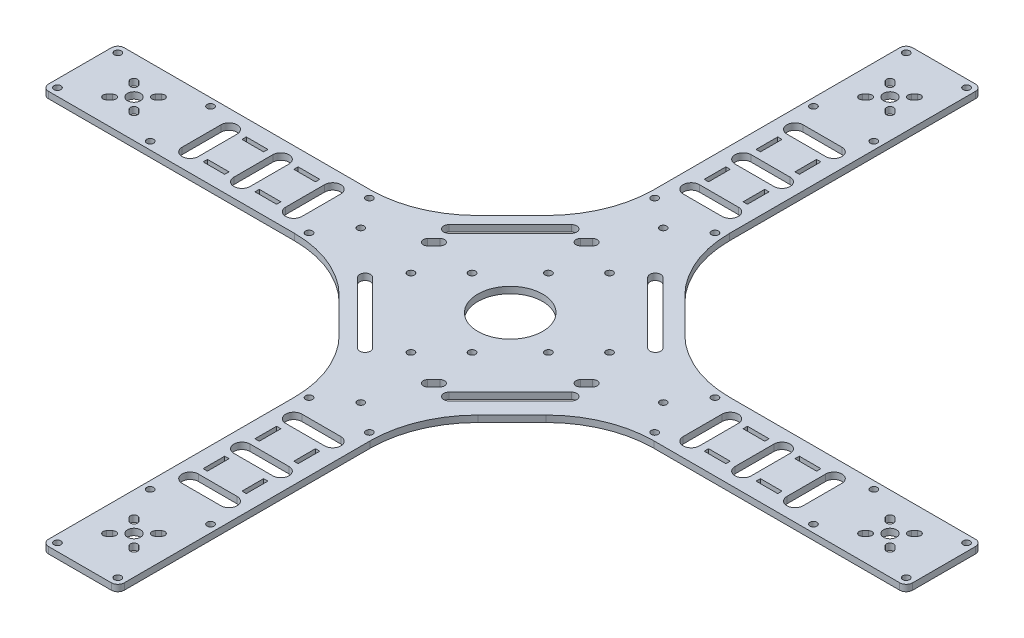
SolidWorks part; units mm, degrees
ref_plane "前视基准面" through (0, 0, 0) normal (0, 0, 1) x (1, 0, 0)
ref_plane "上视基准面" through (0, 0, 0) normal (0, 1, 0) x (1, 0, 0)
ref_plane "右视基准面" through (0, 0, 0) normal (1, 0, 0) x (0, 0, -1)
other "Configuration Table"
sketch "基本底盘" plane through (0, 0, 0) normal (0, 1, 0) x (1, 0, 0)
  line L0 (0, 0) -> (0, -350) construction
  line L1 (4.9497, -4.9497) -> (6.364, -6.364) construction
  line L4 (6.0811, -3.8184) -> (7.4953, -5.2326)
  line L5 (3.8184, -6.0811) -> (5.2326, -7.4953)
  line L6 (-17.5, 25) -> (17.5, 25)
  line L9 (-4.9497, -4.9497) -> (-6.364, -6.364) construction
  line L10 (-3.8184, -6.0811) -> (-5.2326, -7.4953)
  line L11 (-6.0811, -3.8184) -> (-7.4953, -5.2326)
  line L12 (-17.5, 25) -> (-17.5, -25)
  line L15 (-4.9497, 4.9497) -> (-6.364, 6.364) construction
  line L16 (-6.0811, 3.8184) -> (-7.4953, 5.2326)
  line L17 (-3.8184, 6.0811) -> (-5.2326, 7.4953)
  line L18 (17.5, 25) -> (17.5, -25)
  line L21 (4.9497, 4.9497) -> (6.364, 6.364) construction
  line L22 (3.8184, 6.0811) -> (5.2326, 7.4953)
  line L23 (6.0811, 3.8184) -> (7.4953, 5.2326)
  line L24 (0, -25) -> (0, -35)
  line L25 (-9, -35) -> (9, -35) construction
  line L26 (-9, -59) -> (9, -59) construction
  line L27 (-17.5, -25) -> (17.5, -25) construction
  line L28 (-17.5, 25) -> (17.5, -25) construction
  line L29 (17.5, 25) -> (-17.5, -25) construction
  line L30 (-17.5, 25) -> (-13.9645, 21.4645)
  line L31 (-17.5, 0) -> (17.5, 0) construction
  line L32 (-80, -175) -> (80, -175)
  line L33 (0, -95) -> (0, -255)
  line L34 (-32.1447, -127.1447) -> (-47.8553, -142.8553)
  line L35 (32.1447, -222.8553) -> (47.8553, -207.1447)
  line L36 (47.8553, -142.8553) -> (32.1447, -127.1447)
  line L37 (-47.8553, -207.1447) -> (-32.1447, -222.8553)
  line L38 (-13.9645, -21.4645) -> (-13.9645, -95) construction
  line L39 (-17.5, -25) -> (-17.5, -91.7893)
  line L40 (17.5, -25) -> (17.5, -91.7893)
  line L41 (0, -95) -> (0, -105)
  line L42 (-9, -31.25) -> (9, -31.25)
  line L43 (-9, -38.75) -> (9, -38.75)
  line L44 (-9, -55.25) -> (9, -55.25)
  line L45 (-9, -62.75) -> (9, -62.75)
  line L46 (-9, -83) -> (9, -83) construction
  line L47 (-9, -79.25) -> (9, -79.25)
  line L48 (-9, -86.75) -> (9, -86.75)
  line L49 (9, -38.75) -> (9, -55.25)
  line L50 (8, -42) -> (10, -42)
  line L51 (8, -42) -> (8, -52)
  line L52 (10, -42) -> (10, -52)
  line L53 (8, -52) -> (10, -52)
  line L54 (8, -42) -> (10, -52) construction
  line L55 (10, -42) -> (8, -52) construction
  line L56 (8, -66) -> (10, -76) construction
  line L57 (10, -66) -> (8, -76) construction
  line L58 (8, -66) -> (10, -66)
  line L59 (8, -66) -> (8, -76)
  line L60 (8, -76) -> (10, -76)
  line L61 (10, -66) -> (10, -76)
  line L62 (-8, -66) -> (-8, -76)
  line L63 (-8, -76) -> (-10, -76)
  line L64 (-10, -66) -> (-10, -76)
  line L65 (-8, -66) -> (-10, -66)
  line L66 (-8, -52) -> (-10, -52)
  line L67 (-8, -42) -> (-8, -52)
  line L68 (-8, -42) -> (-10, -42)
  line L69 (-10, -42) -> (-10, -52)
  line L70 (200, -157.5) -> (200, -192.5)
  line L71 (200, -157.5) -> (150, -157.5)
  line L72 (200, -192.5) -> (150, -192.5)
  line L73 (150, -175) -> (140, -175)
  line L74 (200, -157.5) -> (196.4645, -161.0355)
  line L75 (136.25, -184) -> (119.75, -184)
  line L76 (133, -183) -> (133, -185)
  line L77 (133, -183) -> (123, -183)
  line L78 (133, -185) -> (123, -185)
  line L79 (123, -183) -> (123, -185)
  line L80 (109, -183) -> (109, -185)
  line L81 (109, -183) -> (99, -183)
  line L82 (99, -183) -> (99, -185)
  line L83 (109, -185) -> (99, -185)
  line L84 (109, -167) -> (99, -167)
  line L85 (99, -167) -> (99, -165)
  line L86 (109, -165) -> (99, -165)
  line L87 (109, -167) -> (109, -165)
  line L88 (123, -167) -> (123, -165)
  line L89 (133, -167) -> (123, -167)
  line L90 (133, -167) -> (133, -165)
  line L91 (133, -165) -> (123, -165)
  line L92 (150, -157.5) -> (150, -192.5) construction
  line L93 (200, -157.5) -> (150, -192.5) construction
  line L94 (200, -192.5) -> (150, -157.5) construction
  line L95 (175, -157.5) -> (175, -192.5) construction
  line L96 (153.5355, -161.0355) -> (80, -161.0355) construction
  line L97 (133, -183) -> (123, -185) construction
  line L98 (133, -185) -> (123, -183) construction
  line L99 (109, -183) -> (99, -185) construction
  line L100 (109, -185) -> (99, -183) construction
  line L101 (150, -157.5) -> (83.2107, -157.5)
  line L102 (150, -192.5) -> (83.2107, -192.5)
  line L103 (170.0503, -179.9497) -> (168.636, -181.364) construction
  line L104 (171.1816, -181.0811) -> (169.7674, -182.4953)
  line L105 (168.9189, -178.8184) -> (167.5047, -180.2326)
  line L106 (170.0503, -170.0503) -> (168.636, -168.636) construction
  line L107 (168.9189, -171.1816) -> (167.5047, -169.7674)
  line L108 (171.1816, -168.9189) -> (169.7674, -167.5047)
  line L109 (179.9497, -170.0503) -> (181.364, -168.636) construction
  line L110 (178.8184, -168.9189) -> (180.2326, -167.5047)
  line L111 (181.0811, -171.1816) -> (182.4953, -169.7674)
  line L112 (179.9497, -179.9497) -> (181.364, -181.364) construction
  line L113 (181.0811, -178.8184) -> (182.4953, -180.2326)
  line L114 (178.8184, -181.0811) -> (180.2326, -182.4953)
  line L115 (140, -166) -> (140, -184) construction
  line L116 (143.75, -166) -> (143.75, -184)
  line L117 (136.25, -166) -> (136.25, -184)
  line L118 (116, -166) -> (116, -184) construction
  line L119 (119.75, -166) -> (119.75, -184)
  line L120 (112.25, -166) -> (112.25, -184)
  line L121 (92, -166) -> (92, -184) construction
  line L122 (95.75, -166) -> (95.75, -184)
  line L123 (88.25, -166) -> (88.25, -184)
  line L124 (17.5, -375) -> (-17.5, -375)
  line L125 (17.5, -375) -> (17.5, -325)
  line L126 (-17.5, -375) -> (-17.5, -325)
  line L127 (0, -325) -> (0, -315)
  line L128 (17.5, -375) -> (13.9645, -371.4645)
  line L129 (-9, -311.25) -> (-9, -294.75)
  line L130 (-8, -308) -> (-10, -308)
  line L131 (-8, -308) -> (-8, -298)
  line L132 (-10, -308) -> (-10, -298)
  line L133 (-8, -298) -> (-10, -298)
  line L134 (-8, -284) -> (-10, -284)
  line L135 (-8, -284) -> (-8, -274)
  line L136 (-8, -274) -> (-10, -274)
  line L137 (-10, -284) -> (-10, -274)
  line L138 (8, -284) -> (8, -274)
  line L139 (8, -274) -> (10, -274)
  line L140 (10, -284) -> (10, -274)
  line L141 (8, -284) -> (10, -284)
  line L142 (8, -298) -> (10, -298)
  line L143 (8, -308) -> (8, -298)
  line L144 (8, -308) -> (10, -308)
  line L145 (10, -308) -> (10, -298)
  line L146 (17.5, -325) -> (-17.5, -325) construction
  line L147 (17.5, -375) -> (-17.5, -325) construction
  line L148 (-17.5, -375) -> (17.5, -325) construction
  line L149 (17.5, -350) -> (-17.5, -350) construction
  line L150 (13.9645, -328.5355) -> (13.9645, -255) construction
  line L151 (-8, -308) -> (-10, -298) construction
  line L152 (-10, -308) -> (-8, -298) construction
  line L153 (-8, -284) -> (-10, -274) construction
  line L154 (-10, -284) -> (-8, -274) construction
  line L155 (17.5, -325) -> (17.5, -258.2107)
  line L156 (-17.5, -325) -> (-17.5, -258.2107)
  line L157 (-4.9497, -345.0503) -> (-6.364, -343.636) construction
  line L158 (-6.0811, -346.1816) -> (-7.4953, -344.7674)
  line L159 (-3.8184, -343.9189) -> (-5.2326, -342.5047)
  line L160 (4.9497, -345.0503) -> (6.364, -343.636) construction
  line L161 (3.8184, -343.9189) -> (5.2326, -342.5047)
  line L162 (6.0811, -346.1816) -> (7.4953, -344.7674)
  line L163 (4.9497, -354.9497) -> (6.364, -356.364) construction
  line L164 (6.0811, -353.8184) -> (7.4953, -355.2326)
  line L165 (3.8184, -356.0811) -> (5.2326, -357.4953)
  line L166 (-4.9497, -354.9497) -> (-6.364, -356.364) construction
  line L167 (-3.8184, -356.0811) -> (-5.2326, -357.4953)
  line L168 (-6.0811, -353.8184) -> (-7.4953, -355.2326)
  line L169 (9, -315) -> (-9, -315) construction
  line L170 (9, -318.75) -> (-9, -318.75)
  line L171 (9, -311.25) -> (-9, -311.25)
  line L172 (9, -291) -> (-9, -291) construction
  line L173 (9, -294.75) -> (-9, -294.75)
  line L174 (9, -287.25) -> (-9, -287.25)
  line L175 (9, -267) -> (-9, -267) construction
  line L176 (9, -270.75) -> (-9, -270.75)
  line L177 (9, -263.25) -> (-9, -263.25)
  line L178 (-200, -192.5) -> (-200, -157.5)
  line L179 (-200, -192.5) -> (-150, -192.5)
  line L180 (-200, -157.5) -> (-150, -157.5)
  line L181 (-150, -175) -> (-140, -175)
  line L182 (-200, -192.5) -> (-196.4645, -188.9645)
  line L183 (-136.25, -166) -> (-119.75, -166)
  line L184 (-133, -167) -> (-133, -165)
  line L185 (-133, -167) -> (-123, -167)
  line L186 (-133, -165) -> (-123, -165)
  line L187 (-123, -167) -> (-123, -165)
  line L188 (-109, -167) -> (-109, -165)
  line L189 (-109, -167) -> (-99, -167)
  line L190 (-99, -167) -> (-99, -165)
  line L191 (-109, -165) -> (-99, -165)
  line L192 (-109, -183) -> (-99, -183)
  line L193 (-99, -183) -> (-99, -185)
  line L194 (-109, -185) -> (-99, -185)
  line L195 (-109, -183) -> (-109, -185)
  line L196 (-123, -183) -> (-123, -185)
  line L197 (-133, -183) -> (-123, -183)
  line L198 (-133, -183) -> (-133, -185)
  line L199 (-133, -185) -> (-123, -185)
  line L200 (-150, -192.5) -> (-150, -157.5) construction
  line L201 (-200, -192.5) -> (-150, -157.5) construction
  line L202 (-200, -157.5) -> (-150, -192.5) construction
  line L203 (-175, -192.5) -> (-175, -157.5) construction
  line L204 (-153.5355, -188.9645) -> (-80, -188.9645) construction
  line L205 (-133, -167) -> (-123, -165) construction
  line L206 (-133, -165) -> (-123, -167) construction
  line L207 (-109, -167) -> (-99, -165) construction
  line L208 (-109, -165) -> (-99, -167) construction
  line L209 (-150, -192.5) -> (-83.2107, -192.5)
  line L210 (-150, -157.5) -> (-83.2107, -157.5)
  line L211 (-170.0503, -170.0503) -> (-168.636, -168.636) construction
  line L212 (-171.1816, -168.9189) -> (-169.7674, -167.5047)
  line L213 (-168.9189, -171.1816) -> (-167.5047, -169.7674)
  line L214 (-170.0503, -179.9497) -> (-168.636, -181.364) construction
  line L215 (-168.9189, -178.8184) -> (-167.5047, -180.2326)
  line L216 (-171.1816, -181.0811) -> (-169.7674, -182.4953)
  line L217 (-179.9497, -179.9497) -> (-181.364, -181.364) construction
  line L218 (-178.8184, -181.0811) -> (-180.2326, -182.4953)
  line L219 (-181.0811, -178.8184) -> (-182.4953, -180.2326)
  line L220 (-179.9497, -170.0503) -> (-181.364, -168.636) construction
  line L221 (-181.0811, -171.1816) -> (-182.4953, -169.7674)
  line L222 (-178.8184, -168.9189) -> (-180.2326, -167.5047)
  line L223 (-140, -184) -> (-140, -166) construction
  line L224 (-143.75, -184) -> (-143.75, -166)
  line L225 (-136.25, -184) -> (-136.25, -166)
  line L226 (-116, -184) -> (-116, -166) construction
  line L227 (-119.75, -184) -> (-119.75, -166)
  line L228 (-112.25, -184) -> (-112.25, -166)
  line L229 (-92, -184) -> (-92, -166) construction
  line L230 (-95.75, -184) -> (-95.75, -166)
  line L231 (-88.25, -184) -> (-88.25, -166)
  line L232 (0, -95) -> (-32.1447, -127.1447)
  line L233 (0, -95) -> (32.1447, -127.1447)
  line L234 (47.8553, -142.8553) -> (80, -175)
  line L235 (47.8553, -207.1447) -> (80, -175)
  line L236 (-80, -175) -> (-47.8553, -207.1447)
  line L237 (-80, -175) -> (-47.8553, -142.8553)
  line L238 (-32.1447, -222.8553) -> (0, -255)
  line L239 (0, -255) -> (32.1447, -222.8553)
  circle A0 centre (0, 0) radius 8 construction
  arc A3 (6.0811, -3.8184) -> (3.8184, -6.0811) centre (4.9497, -4.9497) ccw
  arc A4 (5.2326, -7.4953) -> (7.4953, -5.2326) centre (6.364, -6.364) ccw
  arc A7 (-3.8184, -6.0811) -> (-6.0811, -3.8184) centre (-4.9497, -4.9497) ccw
  arc A8 (-7.4953, -5.2326) -> (-5.2326, -7.4953) centre (-6.364, -6.364) ccw
  arc A11 (-6.0811, 3.8184) -> (-3.8184, 6.0811) centre (-4.9497, 4.9497) ccw
  arc A12 (-5.2326, 7.4953) -> (-7.4953, 5.2326) centre (-6.364, 6.364) ccw
  arc A15 (3.8184, 6.0811) -> (6.0811, 3.8184) centre (4.9497, 4.9497) ccw
  arc A16 (7.4953, 5.2326) -> (5.2326, 7.4953) centre (6.364, 6.364) ccw
  circle A17 centre (0, 0) radius 14 construction
  arc A18 (-9, -31.25) -> (-9, -38.75) centre (-9, -35) ccw
  arc A19 (9, -38.75) -> (9, -31.25) centre (9, -35) ccw
  circle A20 centre (0, 0) radius 3
  circle A21 centre (0, 0) radius 88.9 construction
  circle A22 centre (0, 0) radius 64.77 construction
  circle A23 centre (-13.9645, 21.4645) radius 1.6
  circle A24 centre (13.9645, 21.4645) radius 1.6
  circle A25 centre (13.9645, -21.4645) radius 1.6
  circle A26 centre (-13.9645, -21.4645) radius 1.6
  circle A27 centre (-13.9645, -95) radius 1.6
  circle A28 centre (13.9645, -95) radius 1.6
  circle A29 centre (0, -105) radius 1.6
  arc A30 (-9, -55.25) -> (-9, -62.75) centre (-9, -59) ccw
  arc A31 (9, -62.75) -> (9, -55.25) centre (9, -59) ccw
  arc A32 (-9, -79.25) -> (-9, -86.75) centre (-9, -83) ccw
  arc A33 (9, -86.75) -> (9, -79.25) centre (9, -83) ccw
  circle A34 centre (175, -175) radius 3
  circle A35 centre (196.4645, -161.0355) radius 1.6
  circle A36 centre (196.4645, -188.9645) radius 1.6
  circle A37 centre (153.5355, -188.9645) radius 1.6
  circle A38 centre (153.5355, -161.0355) radius 1.6
  circle A39 centre (80, -161.0355) radius 1.6
  circle A40 centre (80, -188.9645) radius 1.6
  circle A41 centre (175, -175) radius 8 construction
  circle A42 centre (175, -175) radius 14 construction
  circle A43 centre (175, -175) radius 88.9 construction
  circle A44 centre (175, -175) radius 64.77 construction
  circle A45 centre (70, -175) radius 1.6
  arc A46 (171.1816, -181.0811) -> (168.9189, -178.8184) centre (170.0503, -179.9497) ccw
  arc A47 (167.5047, -180.2326) -> (169.7674, -182.4953) centre (168.636, -181.364) ccw
  arc A48 (168.9189, -171.1816) -> (171.1816, -168.9189) centre (170.0503, -170.0503) ccw
  arc A49 (169.7674, -167.5047) -> (167.5047, -169.7674) centre (168.636, -168.636) ccw
  arc A50 (178.8184, -168.9189) -> (181.0811, -171.1816) centre (179.9497, -170.0503) ccw
  arc A51 (182.4953, -169.7674) -> (180.2326, -167.5047) centre (181.364, -168.636) ccw
  arc A52 (181.0811, -178.8184) -> (178.8184, -181.0811) centre (179.9497, -179.9497) ccw
  arc A53 (180.2326, -182.4953) -> (182.4953, -180.2326) centre (181.364, -181.364) ccw
  arc A54 (143.75, -166) -> (136.25, -166) centre (140, -166) ccw
  arc A55 (136.25, -184) -> (143.75, -184) centre (140, -184) ccw
  arc A56 (119.75, -166) -> (112.25, -166) centre (116, -166) ccw
  arc A57 (112.25, -184) -> (119.75, -184) centre (116, -184) ccw
  arc A58 (95.75, -166) -> (88.25, -166) centre (92, -166) ccw
  arc A59 (88.25, -184) -> (95.75, -184) centre (92, -184) ccw
  circle A60 centre (0, -350) radius 3
  circle A61 centre (13.9645, -371.4645) radius 1.6
  circle A62 centre (-13.9645, -371.4645) radius 1.6
  circle A63 centre (-13.9645, -328.5355) radius 1.6
  circle A64 centre (13.9645, -328.5355) radius 1.6
  circle A65 centre (13.9645, -255) radius 1.6
  circle A66 centre (-13.9645, -255) radius 1.6
  circle A67 centre (0, -350) radius 8 construction
  circle A68 centre (0, -350) radius 14 construction
  circle A69 centre (0, -350) radius 88.9 construction
  circle A70 centre (0, -350) radius 64.77 construction
  circle A71 centre (0, -245) radius 1.6
  arc A72 (-6.0811, -346.1816) -> (-3.8184, -343.9189) centre (-4.9497, -345.0503) ccw
  arc A73 (-5.2326, -342.5047) -> (-7.4953, -344.7674) centre (-6.364, -343.636) ccw
  arc A74 (3.8184, -343.9189) -> (6.0811, -346.1816) centre (4.9497, -345.0503) ccw
  arc A75 (7.4953, -344.7674) -> (5.2326, -342.5047) centre (6.364, -343.636) ccw
  arc A76 (6.0811, -353.8184) -> (3.8184, -356.0811) centre (4.9497, -354.9497) ccw
  arc A77 (5.2326, -357.4953) -> (7.4953, -355.2326) centre (6.364, -356.364) ccw
  arc A78 (-3.8184, -356.0811) -> (-6.0811, -353.8184) centre (-4.9497, -354.9497) ccw
  arc A79 (-7.4953, -355.2326) -> (-5.2326, -357.4953) centre (-6.364, -356.364) ccw
  arc A80 (9, -318.75) -> (9, -311.25) centre (9, -315) ccw
  arc A81 (-9, -311.25) -> (-9, -318.75) centre (-9, -315) ccw
  arc A82 (9, -294.75) -> (9, -287.25) centre (9, -291) ccw
  arc A83 (-9, -287.25) -> (-9, -294.75) centre (-9, -291) ccw
  arc A84 (9, -270.75) -> (9, -263.25) centre (9, -267) ccw
  arc A85 (-9, -263.25) -> (-9, -270.75) centre (-9, -267) ccw
  circle A86 centre (-175, -175) radius 3
  circle A87 centre (-196.4645, -188.9645) radius 1.6
  circle A88 centre (-196.4645, -161.0355) radius 1.6
  circle A89 centre (-153.5355, -161.0355) radius 1.6
  circle A90 centre (-153.5355, -188.9645) radius 1.6
  circle A91 centre (-80, -188.9645) radius 1.6
  circle A92 centre (-80, -161.0355) radius 1.6
  circle A93 centre (-175, -175) radius 8 construction
  circle A94 centre (-175, -175) radius 14 construction
  circle A95 centre (-175, -175) radius 88.9 construction
  circle A96 centre (-175, -175) radius 64.77 construction
  circle A97 centre (-70, -175) radius 1.6
  arc A98 (-171.1816, -168.9189) -> (-168.9189, -171.1816) centre (-170.0503, -170.0503) ccw
  arc A99 (-167.5047, -169.7674) -> (-169.7674, -167.5047) centre (-168.636, -168.636) ccw
  arc A100 (-168.9189, -178.8184) -> (-171.1816, -181.0811) centre (-170.0503, -179.9497) ccw
  arc A101 (-169.7674, -182.4953) -> (-167.5047, -180.2326) centre (-168.636, -181.364) ccw
  arc A102 (-178.8184, -181.0811) -> (-181.0811, -178.8184) centre (-179.9497, -179.9497) ccw
  arc A103 (-182.4953, -180.2326) -> (-180.2326, -182.4953) centre (-181.364, -181.364) ccw
  arc A104 (-181.0811, -171.1816) -> (-178.8184, -168.9189) centre (-179.9497, -170.0503) ccw
  arc A105 (-180.2326, -167.5047) -> (-182.4953, -169.7674) centre (-181.364, -168.636) ccw
  arc A106 (-143.75, -184) -> (-136.25, -184) centre (-140, -184) ccw
  arc A107 (-136.25, -166) -> (-143.75, -166) centre (-140, -166) ccw
  arc A108 (-119.75, -184) -> (-112.25, -184) centre (-116, -184) ccw
  arc A109 (-112.25, -166) -> (-119.75, -166) centre (-116, -166) ccw
  arc A110 (-95.75, -184) -> (-88.25, -184) centre (-92, -184) ccw
  arc A111 (-88.25, -166) -> (-95.75, -166) centre (-92, -166) ccw
  arc A112 (17.5, -258.2107) -> (32.1447, -222.8553) centre (67.5, -258.2107) cw
  arc A113 (-17.5, -258.2107) -> (-32.1447, -222.8553) centre (-67.5, -258.2107) ccw
  arc A114 (47.8553, -142.8553) -> (83.2107, -157.5) centre (83.2107, -107.5) ccw
  arc A115 (83.2107, -192.5) -> (47.8553, -207.1447) centre (83.2107, -242.5) ccw
  arc A116 (-47.8553, -207.1447) -> (-83.2107, -192.5) centre (-83.2107, -242.5) ccw
  arc A117 (-47.8553, -142.8553) -> (-83.2107, -157.5) centre (-83.2107, -107.5) cw
  arc A118 (32.1447, -127.1447) -> (17.5, -91.7893) centre (67.5, -91.7893) cw
  arc A119 (-32.1447, -127.1447) -> (-17.5, -91.7893) centre (-67.5, -91.7893) ccw
  point P14 (5.6569, -5.6569)
  point P28 (-5.6569, -5.6569)
  point P34 (0, 0)
  point P42 (-5.6569, 5.6569)
  point P48 (0, -175)
  point P53 (0, -175)
  point P56 (5.6569, 5.6569)
  point P61 (0, 0)
  point P63 (0, 8)
  point P73 (0, -35)
  point P80 (0, -59)
  point P87 (0, -83)
  point P93 (9, -47)
  point P95 (9, -71)
  point P125 (169.3431, -180.6569)
  point P139 (169.3431, -169.3431)
  point P145 (175, -175)
  point P152 (180.6569, -169.3431)
  point P161 (180.6569, -180.6569)
  point P166 (175, -175)
  point P177 (140, -175)
  point P184 (116, -175)
  point P191 (92, -175)
  point P197 (128, -184)
  point P199 (104, -184)
  point P226 (-5.6569, -344.3431)
  point P240 (5.6569, -344.3431)
  point P246 (0, -350)
  point P253 (5.6569, -355.6569)
  point P262 (-5.6569, -355.6569)
  point P267 (0, -350)
  point P278 (0, -315)
  point P285 (0, -291)
  point P292 (0, -267)
  point P298 (-9, -303)
  point P300 (-9, -279)
  point P327 (-169.3431, -169.3431)
  point P341 (-169.3431, -180.6569)
  point P347 (-175, -175)
  point P354 (-180.6569, -180.6569)
  point P363 (-180.6569, -169.3431)
  point P368 (-175, -175)
  point P379 (-140, -175)
  point P386 (-116, -175)
  point P393 (-92, -175)
  point P399 (-128, -166)
  point P401 (-104, -166)
  point P416 (0, -175)
  dimension "D1" = 16
  dimension "D3" = 28
  dimension "D2" = 6
  dimension "D4" = 350
  dimension "D5" = 129.54
  dimension "D9" = 3.2
  dimension "D11" = 3.2
  dimension "D12" = 10
  dimension "D13" = 3.2
  dimension "D14" = 10
  dimension "D15" = 3
  dimension "D20" = 50
  dimension "D6" = 35
  dimension "D7" = 50
  dimension "D8" = 5
  dimension "D10" = 2
  dimension "D16" = 2
  dimension "D17" = 10
  dimension "D18" = 2
  dimension "D19" = 4
extrude "凸台-拉伸1" add sketch "基本底盘" along normal blind 3
fillet "圆角3" radius 3 8 edges at (200, 1.5, 157.5) (200, 1.5, 192.5) (17.5, 1.5, 375) (-17.5, 1.5, 375) (-200, 1.5, 192.5) (-200, 1.5, 157.5) (-17.5, 1.5, -25) (17.5, 1.5, -25)
sketch "草图1" plane through (0, 3, 0) normal (0, 1, 0) x (1, 0, 0)
  line L0 (-43.8547, -181.4697) -> (5.6428, -131.9722) construction
  line L1 (-43.8547, -181.4697) -> (-8.4994, -216.825) construction
  line L2 (5.6428, -131.9722) -> (40.9981, -167.3275) construction
  line L3 (-8.4994, -216.825) -> (40.9981, -167.3275) construction
  line L4 (-43.8547, -181.4697) -> (40.9981, -167.3275) construction
  line L5 (5.6428, -131.9722) -> (-8.4994, -216.825) construction
  line L6 (-43.8547, -181.4697) -> (-39.3043, -186.0201)
  line L9 (-42.0869, -183.2374) -> (-10.2671, -215.0572)
  line L10 (-42.0869, -183.2374) -> (-40.3192, -181.4697)
  line L11 (-26.177, -199.1473) -> (-1.4283, -174.3986) construction
  line L12 (-40.3192, -181.4697) -> (-8.4994, -149.6499) construction
  line L13 (-1.4283, -174.3986) -> (16.2494, -192.0763) construction
  line L14 (16.2494, -192.0763) -> (37.4626, -213.2895)
  line L15 (9.1783, -220.3605) -> (44.5336, -185.0052)
  line L16 (45.9478, -183.591) -> (43.1194, -186.4194) construction
  line L17 (-48.8045, -165.2062) -> (-45.976, -162.3778) construction
  line L18 (47.4328, -185.0759) -> (44.6043, -187.9043)
  line L19 (44.4629, -182.1061) -> (41.6345, -184.9345)
  line L20 (7.7641, -221.7748) -> (10.5925, -218.9463) construction
  line L21 (6.2792, -220.2898) -> (9.1076, -217.4614)
  line L22 (9.249, -223.2597) -> (12.0774, -220.4313)
  line L23 (-47.3195, -166.6911) -> (-44.4911, -163.8627)
  line L24 (-50.2894, -163.7213) -> (-47.461, -160.8929)
  line L25 (-10.6207, -127.0225) -> (-13.4491, -129.8509) construction
  line L26 (-12.1056, -125.5375) -> (-14.934, -128.366)
  line L27 (-9.1358, -128.5074) -> (-11.9642, -131.3358)
  line L28 (-26.177, -199.1473) -> (-35.0159, -207.9862)
  line L29 (-49.158, -193.844) -> (-20.8737, -222.1283) construction
  line L31 (-47.3902, -192.0763) -> (-19.106, -220.3605)
  line L32 (-50.9258, -195.6118) -> (-22.6415, -223.8961)
  line L34 (-20.8737, -126.6689) -> (-49.158, -154.9532) construction
  line L37 (-19.106, -128.4367) -> (-47.3902, -156.7209)
  line L40 (-22.6415, -124.9011) -> (-50.9258, -153.1854)
  line L41 (46.3014, -154.9532) -> (18.0171, -126.6689) construction
  line L42 (44.5336, -156.7209) -> (16.2494, -128.4367)
  line L43 (48.0692, -153.1854) -> (19.7849, -124.9011)
  line L44 (18.0171, -222.1283) -> (46.3014, -193.844) construction
  line L45 (16.2494, -220.3605) -> (44.5336, -192.0763)
  line L46 (19.7849, -223.8961) -> (48.0692, -195.6118)
  circle A1 centre (-40.3192, -181.4697) radius 1.6
  circle A2 centre (-8.4994, -213.2895) radius 1.6
  circle A3 centre (-8.4994, -149.6499) radius 1.6
  circle A4 centre (23.3204, -181.4697) radius 1.6
  circle A5 centre (37.4626, -167.3275) radius 1.6
  circle A6 centre (5.6428, -135.5077) radius 1.6
  circle A7 centre (-26.177, -167.3275) radius 1.6
  circle A8 centre (5.6428, -199.1473) radius 1.6
  arc A9 (47.4328, -185.0759) -> (44.4629, -182.1061) centre (45.9478, -183.591) ccw
  arc A10 (41.6345, -184.9345) -> (44.6043, -187.9043) centre (43.1194, -186.4194) ccw
  arc A11 (6.2792, -220.2898) -> (9.249, -223.2597) centre (7.7641, -221.7748) ccw
  arc A12 (12.0774, -220.4313) -> (9.1076, -217.4614) centre (10.5925, -218.9463) ccw
  arc A13 (-47.3195, -166.6911) -> (-50.2894, -163.7213) centre (-48.8045, -165.2062) cw
  arc A14 (-47.461, -160.8929) -> (-44.4911, -163.8627) centre (-45.976, -162.3778) cw
  arc A15 (-12.1056, -125.5375) -> (-9.1358, -128.5074) centre (-10.6207, -127.0225) cw
  arc A16 (-11.9642, -131.3358) -> (-14.934, -128.366) centre (-13.4491, -129.8509) cw
  circle A17 centre (-1.4283, -174.3986) radius 15
  arc A18 (-47.3902, -192.0763) -> (-50.9258, -195.6118) centre (-49.158, -193.844) ccw
  arc A19 (-22.6415, -223.8961) -> (-19.106, -220.3605) centre (-20.8737, -222.1283) ccw
  arc A26 (-19.106, -128.4367) -> (-22.6415, -124.9011) centre (-20.8737, -126.6689) ccw
  arc A27 (-50.9258, -153.1854) -> (-47.3902, -156.7209) centre (-49.158, -154.9532) ccw
  arc A28 (44.5336, -156.7209) -> (48.0692, -153.1854) centre (46.3014, -154.9532) ccw
  arc A29 (19.7849, -124.9011) -> (16.2494, -128.4367) centre (18.0171, -126.6689) ccw
  arc A30 (16.2494, -220.3605) -> (19.7849, -223.8961) centre (18.0171, -222.1283) ccw
  arc A31 (48.0692, -195.6118) -> (44.5336, -192.0763) centre (46.3014, -193.844) ccw
  point P1 (-1.4283, -174.3986)
  point P6 (-26.177, -199.1473)
  point P32 (26.856, -202.6829)
  point P36 (44.5336, -185.0052)
  point P42 (9.1783, -220.3605)
  point P48 (-47.3902, -163.792)
  point P55 (-12.0349, -128.4367)
  point P64 (0, 0)
  point P66 (-35.0159, -207.9862)
  point P74 (-35.0159, -140.811)
  point P81 (32.1593, -140.811)
  point P88 (32.1593, -207.9862)
  point P93 (-4.9638, -177.9341)
  point P94 (-1.4283, -174.3986)
  dimension "D5" = 45
  dimension "D4" = 3.2
  dimension "D6" = 3.2
  dimension "D8" = 30
  dimension "D9" = 12.5
  dimension "D1" = 70
  dimension "D2" = 50
  dimension "D3" = 2.5
  dimension "D7" = 30
  dimension "D10" = 4
extrude "切除-拉伸1" cut sketch "草图1" against normal blind 10
